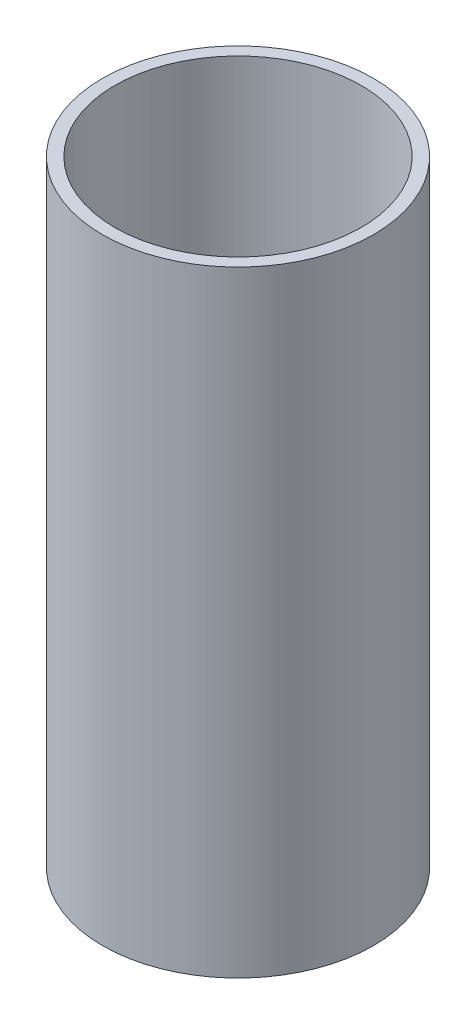
SolidWorks part; units mm, degrees
ref_plane "Front Plane" through (0, 0, 0) normal (0, 0, 1) x (1, 0, 0)
ref_plane "Top Plane" through (0, 0, 0) normal (0, 1, 0) x (1, 0, 0)
ref_plane "Right Plane" through (0, 0, 0) normal (1, 0, 0) x (0, 0, -1)
sketch "Sketch1" plane through (0, 0, 0) normal (0, 1, 0) x (1, 0, 0)
  circle A0 centre (0, 0) radius 50
  circle A1 centre (0, 0) radius 55
  dimension "D1" = 100
  dimension "D2" = 110
extrude "Boss-Extrude1" add sketch "Sketch1" along normal blind 250
